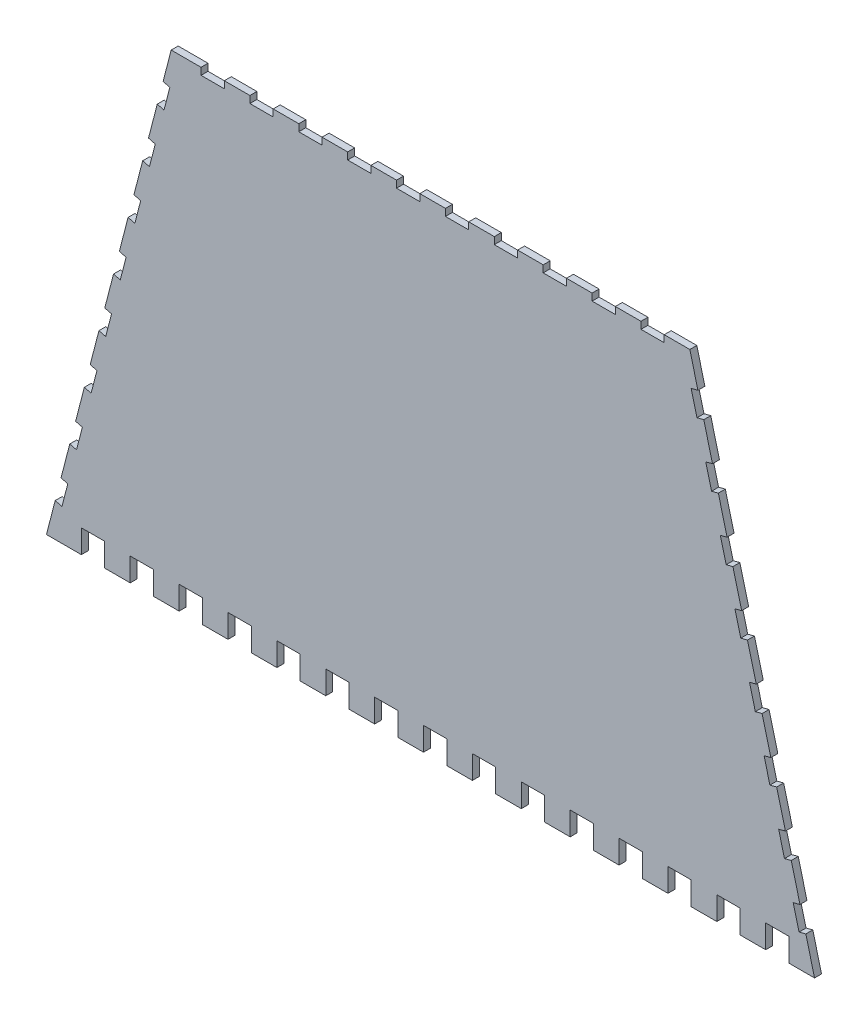
SolidWorks part; units mm, degrees
ref_plane "Front Plane" through (0, 0, 0) normal (0, 0, 1) x (1, 0, 0)
ref_plane "Top Plane" through (0, 0, 0) normal (0, 1, 0) x (1, 0, 0)
ref_plane "Right Plane" through (0, 0, 0) normal (1, 0, 0) x (0, 0, -1)
sketch "Sketch2" plane through (0, 0, 0) normal (0, 0, 1) x (1, 0, 0)
  line L0 (-111.4102, 164.3501) -> (111.4102, 164.3501)
  line L1 (111.4102, 164.3501) -> (165, -42.7051)
  line L2 (165, -42.7051) -> (-165, -42.7051)
  line L3 (-165, -42.7051) -> (-111.4102, 164.3501)
  dimension "D1" = 330
  dimension "D2" = 213.8779
  dimension "D3" = 222.8203
extrude "Boss-Extrude1" add sketch "Sketch2" along normal blind 3 contours L1 L2 L3 L0
sketch "Sketch3" plane through (0, 0, 0) normal (0, 0, -1) x (-1, 0, 0)
  line L0 (-161.2416, -28.1836) -> (-158.3373, -28.9353)
  line L1 (-111.4102, 164.3501) -> (-165, -42.7051) construction
  line L2 (-158.3373, -28.9353) -> (-155.8316, -19.2543)
  line L3 (-155.8316, -19.2543) -> (-158.7359, -18.5026)
  line L4 (-158.7359, -18.5026) -> (-161.2416, -28.1836)
  dimension "D1" = 10
  dimension "D2" = 15
extrude "Cut-Extrude1" cut sketch "Sketch3" against normal blind 3
pattern_linear "LPattern1" count 8 spacing 25 along (-0.2506, 0.9681, 0) of "Cut-Extrude1"
mirror "Mirror1" about plane through (0, 0, 0) normal (1, 0, 0) of "LPattern1", "Cut-Extrude1"
sketch "Sketch4" plane through (0, 0, 0) normal (0, 0, -1) x (-1, 0, 0)
  line L0 (-154, -42.7051) -> (-154, -32.7051)
  line L1 (-165, -42.7051) -> (165, -42.7051) construction
  line L2 (-154, -32.7051) -> (-144, -32.7051)
  line L3 (-144, -32.7051) -> (-144, -42.7051)
  dimension "D1" = 10
  dimension "D2" = 10
  dimension "D3" = 11
extrude "Cut-Extrude3" cut sketch "Sketch4" against normal blind 3 and the other way through all flip side to cut contours L0 L2 L3
pattern_linear "LPattern2" count 15 spacing 21 along (-1, 0, 0) of "Cut-Extrude3"
sketch "Sketch5" plane through (0, 0, 0) normal (0, 0, -1) x (-1, 0, 0)
  line L0 (-100.4102, 164.3501) -> (-100.4102, 161.3501)
  line L1 (111.4102, 164.3501) -> (-111.4102, 164.3501) construction
  line L2 (-100.4102, 161.3501) -> (-90.4102, 161.3501)
  line L3 (-90.4102, 161.3501) -> (-90.4102, 164.3501)
  dimension "D1" = 10
  dimension "D2" = 3
  dimension "D3" = 11
extrude "Cut-Extrude5" cut sketch "Sketch5" against normal blind 3 and the other way through all contours L0 L2 L3
pattern_linear "LPattern3" count 10 spacing 21 along (-1, 0, 0) of "Cut-Extrude5"
